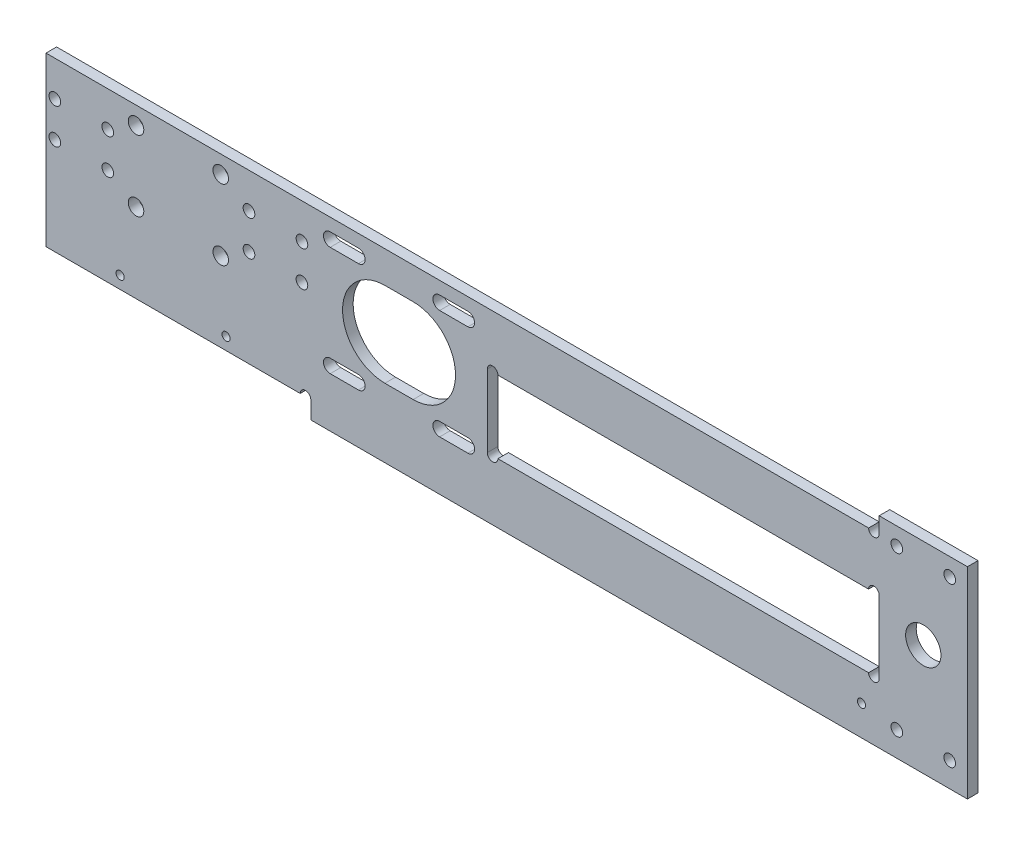
SolidWorks part; units mm, degrees
material "Thornel Mat VMA"
ref_plane "前视基准面" through (0, 0, 0) normal (0, 0, 1) x (1, 0, 0)
ref_plane "上视基准面" through (0, 0, 0) normal (0, 1, 0) x (1, 0, 0)
ref_plane "右视基准面" through (0, 0, 0) normal (1, 0, 0) x (0, 0, -1)
sketch "草图1" plane through (0, 0, 0) normal (0, 0, 1) x (1, 0, 0)
  line L1 (0, 0) -> (75, 0)
  line L2 (0, 0) -> (0, 30)
  line L3 (0, 30) -> (75, 30)
  line L4 (75, 0) -> (75, 30)
  dimension "D1" = 75
  dimension "D2" = 30
extrude "凸台-拉伸1" add sketch "草图1" along normal blind 3
sketch "草图2" plane through (0, 0, 3) normal (0, 0, 1) x (1, 0, 0)
  line L0 (0, 30) -> (75, 0)
  line L2 (25.5, 25) -> (49.5, 25)
  line L3 (25.5, 25) -> (25.5, 5)
  line L4 (25.5, 5) -> (49.5, 5)
  line L5 (49.5, 25) -> (49.5, 5)
  line L6 (25.5, 25) -> (49.5, 5) construction
  line L7 (25.5, 5) -> (49.5, 25) construction
  point P4 (37.5, 15)
  dimension "D1" = 24
  dimension "D2" = 20
sketch "草图3" plane through (0, 0, 3) normal (0, 0, 1) x (1, 0, 0)
  point P0 (25.5, 25)
  point P3 (49.5, 25)
  point P6 (49.5, 5)
  point P9 (25.5, 5)
hole_wizard "孔1" positions "草图3" profile "草图4" legacy end condition up to next
sketch "草图4" plane through (25.5, 25, 3) normal (1, 0, 0) x (0, -1, 0)
  line L0 (0, 0) -> (0, 3)
  line L1 (0, 3) -> (2.2, 3)
  line L2 (2.2, 3) -> (2.2, 0)
  line L3 (2.2, 0) -> (0, 0)
  line L4 (0, 110) -> (0, -10) construction
  dimension "直径" = 4.4
  dimension "深度" = 3
sketch "草图5" plane through (0, 0, 3) normal (0, 0, 1) x (1, 0, 0)
  line L0 (75, 30) -> (0, 30) construction
  line L1 (20, 0) -> (55, 0)
  line L2 (20, 0) -> (20, 30)
  line L3 (20, 30) -> (55, 30)
  line L4 (55, 0) -> (55, 30)
  line L5 (20, 0) -> (55, 30) construction
  line L6 (20, 30) -> (55, 0) construction
  line L7 (0, 15) -> (20, 15)
  line L8 (0, 30) -> (0, 0) construction
  line L9 (55, 15) -> (75, 15)
  line L10 (75, 0) -> (75, 30) construction
  line L12 (2.5, 10) -> (17.5, 10)
  line L13 (2.5, 10) -> (2.5, 20)
  line L14 (2.5, 20) -> (17.5, 20)
  line L15 (17.5, 10) -> (17.5, 20)
  line L16 (2.5, 10) -> (17.5, 20) construction
  line L17 (2.5, 20) -> (17.5, 10) construction
  line L18 (57.5, 10) -> (72.5, 10)
  line L19 (57.5, 10) -> (57.5, 20)
  line L20 (57.5, 20) -> (72.5, 20)
  line L21 (72.5, 10) -> (72.5, 20)
  line L22 (57.5, 10) -> (72.5, 20) construction
  line L23 (57.5, 20) -> (72.5, 10) construction
  point P0 (37.5, 15)
  point P16 (10, 15)
  point P21 (65, 15)
  dimension "D1" = 35
  dimension "D2" = 15
  dimension "D3" = 10
  dimension "D4" = 15
  dimension "D5" = 10
sketch "草图6" plane through (0, 0, 3) normal (0, 0, 1) x (1, 0, 0)
  point P0 (2.5, 20)
  point P3 (17.5, 20)
  point P6 (17.5, 10)
  point P9 (2.5, 10)
  point P12 (57.5, 10)
  point P15 (57.5, 20)
  point P18 (72.5, 20)
  point P21 (72.5, 10)
hole_wizard "孔2" positions "草图6" profile "草图7" legacy end condition up to next
sketch "草图7" plane through (2.5, 20, 3) normal (1, 0, 0) x (0, -1, 0)
  line L0 (0, 0) -> (0, 3)
  line L1 (0, 3) -> (1.65, 3)
  line L2 (1.65, 3) -> (1.65, 0)
  line L3 (1.65, 0) -> (0, 0)
  line L4 (0, 110) -> (0, -10) construction
  dimension "直径" = 3.3
  dimension "深度" = 3
sketch "草图8" plane through (0, 0, 0) normal (0, 0, -1) x (-1, 0, 0)
  line L1 (0, 30) -> (45, 30)
  line L2 (0, 30) -> (0, -12)
  line L3 (0, -12) -> (45, -12)
  line L4 (45, 30) -> (45, -12)
  dimension "D1" = 45
  dimension "D2" = 42
extrude "凸台-拉伸2" add sketch "草图8" against normal blind 3
sketch "草图9" plane through (0, 0, 3) normal (0, 0, 1) x (1, 0, 0)
  line L0 (0, -12) -> (-45, -12) construction
  line L1 (-45, 30) -> (-3, 30)
  line L2 (-45, 30) -> (-45, -12)
  line L3 (-45, -12) -> (-3, -12)
  line L4 (-3, 30) -> (-3, -12)
  line L5 (-45, 30) -> (-3, -12)
  line L7 (-39.5, 24.5) -> (-8.5, 24.5)
  line L8 (-39.5, 24.5) -> (-39.5, -6.5)
  line L9 (-39.5, -6.5) -> (-8.5, -6.5)
  line L10 (-8.5, 24.5) -> (-8.5, -6.5)
  line L11 (-39.5, 24.5) -> (-8.5, -6.5) construction
  line L12 (-39.5, -6.5) -> (-8.5, 24.5) construction
  point P7 (-24, 9)
  dimension "D1" = 42
  dimension "D2" = 31
sketch "草图10" plane through (0, 0, 3) normal (0, 0, 1) x (1, 0, 0)
  point P0 (-39.5, 24.5)
  point P3 (-8.5, 24.5)
  point P6 (-8.5, -6.5)
  point P9 (-39.5, -6.5)
hole_wizard "孔3" positions "草图10" profile "草图11" legacy end condition up to next
sketch "草图11" plane through (-39.5, 24.5, 3) normal (1, 0, 0) x (0, -1, 0)
  line L0 (0, 0) -> (0, 3)
  line L1 (0, 3) -> (1.9, 3)
  line L2 (1.9, 3) -> (1.9, 0)
  line L3 (1.9, 0) -> (0, 0)
  line L4 (0, 110) -> (0, -10) construction
  dimension "直径" = 3.8
  dimension "深度" = 3
sketch "草图12" plane through (0, 0, 0) normal (0, 0, -1) x (-1, 0, 0)
  circle A0 centre (24, 9) radius 11.5
  dimension "D1" = 23
sketch "草图13" plane through (0, 0, 0) normal (0, 0, -1) x (-1, 0, 0)
  line L0 (45, -12) -> (3, -12) construction
  line L1 (45, 30) -> (60, 30)
  line L2 (45, 30) -> (45, -12)
  line L3 (45, -12) -> (60, -12)
  line L4 (60, 30) -> (60, -12)
  dimension "D1" = 15
extrude "凸台-拉伸3" add sketch "草图13" against normal blind 3
sketch "草图14" plane through (0, 0, 0) normal (0, 0, -1) x (-1, 0, 0)
  line L0 (39.5, -6.5) -> (8.5, -6.5) construction
  line L1 (39.5, 24.5) -> (54.5, 24.5)
  line L2 (39.5, 24.5) -> (39.5, -6.5)
  line L3 (39.5, -6.5) -> (54.5, -6.5)
  line L4 (54.5, 24.5) -> (54.5, -6.5)
  line L5 (39.5, 24.5) -> (8.5, 24.5) construction
  line L7 (8.5, 26.4) -> (23.5, 26.4)
  line L8 (8.5, 26.4) -> (8.5, 22.6)
  line L9 (8.5, 22.6) -> (23.5, 22.6)
  line L10 (23.5, 26.4) -> (23.5, 22.6)
  line L11 (8.5, -4.6) -> (23.5, -4.6)
  line L12 (8.5, -4.6) -> (8.5, -8.4)
  line L13 (8.5, -8.4) -> (23.5, -8.4)
  line L14 (23.5, -4.6) -> (23.5, -8.4)
  line L15 (39.5, 26.4) -> (54.5, 26.4)
  line L16 (39.5, 26.4) -> (39.5, 22.6)
  line L17 (39.5, 22.6) -> (54.5, 22.6)
  line L18 (54.5, 26.4) -> (54.5, 22.6)
  line L19 (39.5, -4.6) -> (54.5, -4.6)
  line L20 (39.5, -4.6) -> (39.5, -8.4)
  line L21 (39.5, -8.4) -> (54.5, -8.4)
  line L22 (54.5, -4.6) -> (54.5, -8.4)
  circle A0 centre (23.5, 24.5) radius 1.9
  circle A1 centre (54.5, 24.5) radius 1.9
  circle A2 centre (54.5, -6.5) radius 1.9
  circle A3 centre (23.5, -6.5) radius 1.9
  circle A4 centre (8.5, 24.5) radius 1.9
  circle A5 centre (8.5, -6.5) radius 1.9
  circle A6 centre (39.5, 24.5) radius 1.9
  circle A7 centre (39.5, -6.5) radius 1.9
  circle M6 centre (39.5, 24.5) radius 1.9
  circle M7 centre (8.5, 24.5) radius 1.9
  circle M8 centre (8.5, -6.5) radius 1.9
  circle M9 centre (39.5, -6.5) radius 1.9
  dimension "D2" = 3.8
  dimension "D3" = 3.8
  dimension "D4" = 3.8
  dimension "D5" = 3.8
  dimension "D8" = 3.8
  dimension "D9" = 3.8
  dimension "D10" = 3.8
  dimension "D11" = 3.8
  dimension "D1" = 15
  dimension "D6" = 15
  dimension "D7" = 15
extrude "切除-拉伸3" cut sketch "草图14" against normal blind 3 contours A0 L7 L9 M7 | L10 A0 | L8 M7 | A3 L11 L13 M8 | L12 M8 | L14 A3 | L14 A3 | L12 M8 | L8 M7 | L10 A0 | A1 L15 L1 M6 | A1 L1 L17 M6 | L1 L2 M6 | L16 L1 M6 | L16 L2 M6 | L4 A1 L18 | L1 A1 L4 | L18 A1 L1 | A2 L19 L3 M9 | A2 L3 L21 M9 | L3 A2 L22 | L4 A2 L3 | L22 A2 L4 | L3 L20 M9 | L2 L3 M9 | L20 L2 M9
sketch "草图16" plane through (0, 0, 0) normal (0, 0, -1) x (-1, 0, 0)
  line L0 (24, 9) -> (39, 9)
  line L1 (39.5, 24.5) -> (39.5, -6.5) construction
  line L2 (24, 20.5041) -> (39.5, 20.5041)
  line L3 (24, 20.5041) -> (24, -2.4891)
  line L4 (24, -2.4891) -> (39.5, -2.4891)
  line L5 (39.5, 20.5041) -> (39.5, -2.4891)
  circle A0 centre (39, 9) radius 11.5
  circle A1 centre (24, 9) radius 11.5041
  dimension "D2" = 23
  dimension "D3" = 23.0082
  dimension "D1" = 15
extrude "切除-拉伸5" cut sketch "草图16" against normal blind 3
sketch "草图17" plane through (0, 0, 0) normal (0, 0, -1) x (-1, 0, 0)
  line L0 (24, 20.5041) -> (24, -2.5041)
  circle A0 centre (24, 9) radius 11.5041
  line M1 (24, -2.4891) -> (24, 20.5041)
extrude "切除-拉伸6" cut sketch "草图17" against normal blind 3 contours A0 L0 M1
sketch "草图18" plane through (0, 0, 0) normal (0, 0, -1) x (-1, 0, 0)
  line L0 (24, -2.5041) -> (-75, -2.5041)
  line L1 (-75, 0) -> (0, 0)
  line L2 (-75, 0) -> (-75, -2.5041)
  line L3 (0, 0) -> (0, -2.5041)
  line L4 (24, -2.5041) -> (-236, -2.5041)
  line L5 (24, -2.5041) -> (24, -22.5041)
  line L6 (24, -22.5041) -> (-236, -22.5041)
  line L7 (-236, -2.5041) -> (-236, -22.5041)
  line L8 (0, 0) -> (0, -12) construction
  line L9 (0, -2.5041) -> (0, -22.5041)
  line L10 (-75, -2.5041) -> (-75, -22.5041)
  line L11 (-236, -5.5041) -> (24, -5.5041)
  line L12 (-236, -5.5041) -> (-236, -22.5041)
  line L13 (-236, -22.5041) -> (24, -22.5041)
  line L14 (24, -5.5041) -> (24, -22.5041)
  circle A0 centre (24, 9) radius 11.5
  line M37 (-75, 0) -> (0, 0)
  line M38 (0, 0) -> (0, -12)
  dimension "D1" = 23
  dimension "D2" = 99
  dimension "D3" = 260
  dimension "D4" = 20
  dimension "D5" = 17
extrude "凸台-拉伸4" add sketch "草图18" against normal blind 3 contours L2 L0 M37 M38 | L10 L11 L0 M38 | L11 L10 L6 L9 | L11 L7 L6 L10
sketch "草图19" plane through (0, 0, 3) normal (0, 0, 1) x (1, 0, 0)
  line L0 (0, -22.5041) -> (236, -22.5041) construction
  line L1 (236, -5.5041) -> (46, -5.5041)
  line L2 (236, -5.5041) -> (236, -22.5041)
  line L3 (236, -22.5041) -> (46, -22.5041)
  line L4 (46, -5.5041) -> (46, -22.5041)
  line L5 (236, -14.0041) -> (46, -14.0041)
  point P9 (231, -14.0041)
  point P10 (51, -14.0041)
  dimension "D1" = 190
  dimension "D2" = 5
  dimension "D3" = 5
sketch "草图20" plane through (0, 0, 3) normal (0, 0, 1) x (1, 0, 0)
  point P0 (80, -14.0041)
  point P2 (260, -14.0041)
  point P4 (231, -14.0041)
  point P7 (51, -14.0041)
hole_wizard "孔4" positions "草图20" profile "草图21" legacy
sketch "草图21" plane through (51, -14.0041, 3) normal (1, 0, 0) x (0, -1, 0)
  line L0 (0, 0) -> (0, 3)
  line L1 (0, 3) -> (1.15, 3)
  line L2 (1.15, 3) -> (1.15, 0)
  line L3 (1.15, 0) -> (0, 0)
  line L4 (0, 110) -> (0, -10) construction
  dimension "直径" = 2.3
  dimension "深度" = 3
sketch "草图22" plane through (0, 0, 0) normal (0, 0, -1) x (-1, 0, 0)
  line L1 (-236, 19.4959) -> (-261, 19.4959)
  line L2 (-236, 19.4959) -> (-236, -22.5041)
  line L3 (-236, -22.5041) -> (-261, -22.5041)
  line L4 (-261, 19.4959) -> (-261, -22.5041)
  line L5 (-236, -5.5041) -> (-236, -22.5041) construction
  line L6 (-236, -22.5041) -> (-46, -22.5041) construction
  dimension "D1" = 42
  dimension "D2" = 25
extrude "凸台-拉伸5" add sketch "草图22" against normal up to vertex (3 mm away) up to point (236, -22.5041, 3)
sketch "草图23" plane through (0, 0, 0) normal (0, 0, -1) x (-1, 0, 0)
  line L0 (-261, 19.4959) -> (-261, -22.5041) construction
  line L1 (-261, 19.4959) -> (-236, 19.4959)
  line L2 (-261, 19.4959) -> (-261, -5.5041)
  line L3 (-261, -5.5041) -> (-236, -5.5041)
  line L4 (-236, 19.4959) -> (-236, -5.5041)
  line L5 (-236, -5.5041) -> (-236, 19.4959) construction
  line L6 (-236, 19.4959) -> (-261, 19.4959) construction
  line L7 (-236, 19.4959) -> (-261, -5.5041)
  line L8 (-248.5, 6.9959) -> (-248.5, 8.9959)
  dimension "D1" = 2
sketch "草图24" plane through (0, 0, 0) normal (0, 0, -1) x (-1, 0, 0)
  point P0 (-277.5, 6.9959)
  point P2 (-248.5, 8.9959)
hole_wizard "孔5" positions "草图24" profile "草图25" legacy end condition up to next
sketch "草图25" plane through (248.5, 8.9959, 0) normal (1, 0, 0) x (0, 1, 0)
  line L0 (0, 0) -> (0, 3)
  line L1 (0, 3) -> (5, 3)
  line L2 (5, 3) -> (5, 0)
  line L3 (5, 0) -> (0, 0)
  line L4 (0, 110) -> (0, -10) construction
  dimension "直径" = 10
  dimension "深度" = 3
sketch "草图26" plane through (0, 0, 0) normal (0, 0, -1) x (-1, 0, 0)
  line L1 (-261, -10.5041) -> (-251, -10.5041)
  line L2 (-261, -10.5041) -> (-261, -20.5041)
  line L3 (-261, -20.5041) -> (-251, -20.5041)
  line L4 (-251, -10.5041) -> (-251, -20.5041)
  line L5 (-261, -10.5041) -> (-251, -20.5041)
  line L6 (-236, -10.5041) -> (-246, -10.5041)
  line L7 (-236, -10.5041) -> (-236, -20.5041)
  line L8 (-236, -20.5041) -> (-246, -20.5041)
  line L9 (-246, -10.5041) -> (-246, -20.5041)
  line L10 (-236, -10.5041) -> (-246, -20.5041)
  line L11 (-261, -5.5041) -> (-236, -5.5041) construction
  line L12 (-261, 19.4959) -> (-261, -22.5041) construction
  line L13 (-236, -5.5041) -> (-236, -22.5041) construction
  dimension "D1" = 10
  dimension "D2" = 10
  dimension "D3" = 10
  dimension "D4" = 10
  dimension "D5" = 5
  dimension "D6" = 5
sketch "草图29" plane through (0, 0, 0) normal (0, 0, -1) x (-1, 0, 0)
  line L0 (-261, -10.5041) -> (-251, -20.5041) construction
  line L1 (-236, -10.5041) -> (-246, -20.5041) construction
  point P0 (-285, -15.5041)
  point P2 (-270, -15.5041)
  point P3 (-285, -15.5041)
  point P6 (-285, -15.5041)
  point P9 (-256, -15.5041)
  point P13 (-241, -15.5041)
hole_wizard "孔7" positions "草图29" profile "草图30" legacy end condition up to next
sketch "草图30" plane through (241, -15.5041, 0) normal (1, 0, 0) x (0, 1, 0)
  line L0 (0, 0) -> (0, 3.001)
  line L1 (0, 3.001) -> (1.65, 3.001)
  line L2 (1.65, 3.001) -> (1.65, 0)
  line L3 (1.65, 0) -> (0, 0)
  line L4 (0, 110) -> (0, -10) construction
  dimension "直径" = 3.3
  dimension "深度" = 3.001
sketch "草图31" plane through (0, 0, 0) normal (0, 0, -1) x (-1, 0, 0)
  line L0 (-236, 19.4959) -> (-236, -5.5041) construction
  line L1 (-261, 19.4959) -> (-236, 19.4959)
  line L2 (-261, 19.4959) -> (-261, 34.4959)
  line L3 (-261, 34.4959) -> (-236, 34.4959)
  line L4 (-236, 19.4959) -> (-236, 34.4959)
  line L5 (-261, 19.4959) -> (-261, -5.5041) construction
  line L6 (-261, 19.4959) -> (-236, 19.4959) construction
  dimension "D1" = 15
extrude "凸台-拉伸6" add sketch "草图31" against normal blind 3
sketch "草图32" plane through (0, 0, 0) normal (0, 0, -1) x (-1, 0, 0)
  line L0 (-261, 34.4959) -> (-261, -22.5041) construction
  line L1 (-261, 34.4959) -> (-251, 34.4959)
  line L2 (-261, 34.4959) -> (-261, 24.4959)
  line L3 (-261, 24.4959) -> (-251, 24.4959)
  line L4 (-251, 34.4959) -> (-251, 24.4959)
  line L5 (-236, 34.4959) -> (-261, 34.4959) construction
  line L6 (-236, -5.5041) -> (-236, 34.4959) construction
  line L7 (-236, 34.4959) -> (-246, 34.4959)
  line L8 (-236, 34.4959) -> (-236, 24.4959)
  line L9 (-236, 24.4959) -> (-246, 24.4959)
  line L10 (-246, 34.4959) -> (-246, 24.4959)
  line L11 (-261, 34.4959) -> (-251, 24.4959)
  line L12 (-236, 34.4959) -> (-246, 24.4959)
  dimension "D1" = 10
  dimension "D2" = 10
  dimension "D3" = 10
  dimension "D4" = 10
sketch "草图33" plane through (0, 0, 0) normal (0, 0, -1) x (-1, 0, 0)
  line L0 (-261, 34.4959) -> (-251, 24.4959) construction
  line L1 (-236, 34.4959) -> (-246, 24.4959) construction
  point P0 (-285, 29.4959)
  point P2 (-270, 29.4959)
  point P3 (-256, 29.4959)
  point P7 (-241, 29.4959)
hole_wizard "孔8" positions "草图33" profile "草图34" legacy end condition up to next
sketch "草图34" plane through (241, 29.4959, 0) normal (1, 0, 0) x (0, 1, 0)
  line L0 (0, 0) -> (0, 3)
  line L1 (0, 3) -> (1.65, 3)
  line L2 (1.65, 3) -> (1.65, 0)
  line L3 (1.65, 0) -> (0, 0)
  line L4 (0, 110) -> (0, -10) construction
  dimension "直径" = 3.3
  dimension "深度" = 3
sketch "草图35" plane through (0, 0, 0) normal (0, 0, -1) x (-1, 0, 0)
  line L0 (24, 9) -> (-261, 9)
  line L1 (-236, -22.5041) -> (-46, -22.5041) construction
  line L2 (-261, 19.4959) -> (-261, -5.5041) construction
sketch "草图36" plane through (0, 0, 0) normal (0, 0, -1) x (-1, 0, 0)
  line L0 (-236, 19.4959) -> (-236, -5.5041) construction
  line L1 (-75, 30) -> (-236, 30)
  line L2 (-75, 30) -> (-75, 15)
  line L3 (-75, 15) -> (-236, 15)
  line L4 (-236, 30) -> (-236, 15)
  dimension "D1" = 15
extrude "凸台-拉伸7" add sketch "草图36" against normal blind 3
sketch "草图37" plane through (0, 0, 0) normal (0, 0, -1) x (-1, 0, 0)
  line L0 (-51, -14.0041) -> (-21, -14.0041)
  dimension "D1" = 30
sketch "草图38" plane through (0, 0, 0) normal (0, 0, -1) x (-1, 0, 0)
  point P0 (-21, -14.0041)
hole_wizard "孔9" positions "草图38" profile "草图39" legacy end condition up to next
sketch "草图39" plane through (21, -14.0041, 0) normal (1, 0, 0) x (0, 1, 0)
  line L0 (0, 0) -> (0, 3)
  line L1 (0, 3) -> (1.15, 3)
  line L2 (1.15, 3) -> (1.15, 0)
  line L3 (1.15, 0) -> (0, 0)
  line L4 (0, 110) -> (0, -10) construction
  dimension "直径" = 2.3
  dimension "深度" = 3
sketch "草图40" plane through (0, 0, 0) normal (0, 0, -1) x (-1, 0, 0)
  line L0 (39.5, -6.5) -> (8.5, 24.5) construction
  line L1 (24, 21) -> (39, 21)
  line L2 (24, -3) -> (39, -3)
  circle A0 centre (24, 9) radius 12
  circle A1 centre (39, 9) radius 12
  dimension "D1" = 24
  dimension "D2" = 24
extrude "切除-拉伸7" cut sketch "草图40" against normal blind 10 contours A1 A0 | A0 A1 | A1 L1 A0 | A1 A0 | A1 A0 L2
sketch "草图41" plane through (0, 0, 0) normal (0, 0, -1) x (-1, 0, 0)
  line L0 (24, 9) -> (-261, 9) construction
  line L1 (-125, -12) -> (-75, -12)
  line L2 (-125, -12) -> (-125, 30)
  line L3 (-125, 30) -> (-75, 30)
  line L4 (-75, -12) -> (-75, 30)
  line L5 (-125, -12) -> (-75, 30) construction
  line L6 (-125, 30) -> (-75, -12) construction
  line L7 (-75, -5.5041) -> (-75, 15) construction
  line L8 (-236, 15) -> (-75, 15) construction
  line L9 (-125, 15) -> (-75, 15)
  line L10 (-125, 15) -> (-125, -5.5041)
  line L11 (-125, -5.5041) -> (-75, -5.5041)
  line L12 (-75, 15) -> (-75, -5.5041)
  point P0 (-100, 9)
  dimension "D1" = 50
  dimension "D2" = 42
extrude "凸台-拉伸8" add sketch "草图41" against normal blind 3 contours L2 L11 L4 L9
sketch "草图42" plane through (0, 0, 0) normal (0, 0, -1) x (-1, 0, 0)
  line L0 (-125, -5.5041) -> (-125, 30)
  line L1 (-236, 30) -> (60, 30) construction
  line L2 (-125, 30) -> (-83, -12)
  line L3 (-125, 30) -> (-75, 30)
  line L4 (-125, 30) -> (-125, -12)
  line L5 (-125, -12) -> (-75, -12)
  line L6 (-75, 30) -> (-75, -12)
  line L7 (-125, 30) -> (-83, 30)
  line L8 (-125, 30) -> (-125, -12)
  line L9 (-125, -12) -> (-83, -12)
  line L10 (-83, 30) -> (-83, -12)
  line L11 (-88.5, 24.5) -> (-80.5, 24.5)
  line L12 (-119.5, -6.5) -> (-88.5, -6.5)
  line L13 (-119.5, -6.5) -> (-119.5, 24.5)
  line L14 (-119.5, 24.5) -> (-88.5, 24.5)
  line L15 (-88.5, -6.5) -> (-88.5, 24.5)
  line L16 (-119.5, -6.5) -> (-88.5, 24.5) construction
  line L17 (-119.5, 24.5) -> (-88.5, -6.5) construction
  line L18 (-88.5, -6.5) -> (-80.5, -6.5)
  line L19 (-104, 9) -> (-96, 9)
  line L20 (24, 9) -> (-261, 9) construction
  point P10 (-104, 9)
  point P15 (-111.5, 24.5)
  point P18 (-111.5, -6.5)
  dimension "D1" = 50
  dimension "D2" = 42
  dimension "D3" = 42
  dimension "D4" = 31
  dimension "D5" = 8
  dimension "D6" = 8
  dimension "D7" = 8
  dimension "D8" = 8
  dimension "D9" = 8
sketch "草图44" plane through (0, 0, 0) normal (0, 0, -1) x (-1, 0, 0)
  point P0 (-119.5, 24.5)
  point P3 (-111.5, 24.5)
  point P6 (-88.5, 24.5)
  point P9 (-80.5, 24.5)
  point P12 (-88.5, -6.5)
  point P15 (-80.5, -6.5)
  point P18 (-119.5, -6.5)
  point P21 (-111.5, -6.5)
hole_wizard "孔10" positions "草图44" profile "草图45" legacy end condition through all
sketch "草图45" plane through (119.5, 24.5, 0) normal (1, 0, 0) x (0, 1, 0)
  line L0 (0, 0) -> (0, 3)
  line L1 (0, 3) -> (1.9, 3)
  line L2 (1.9, 3) -> (1.9, 0)
  line L3 (1.9, 0) -> (0, 0)
  line L4 (0, 110) -> (0, -10) construction
  dimension "直径" = 3.8
  dimension "深度" = 3
sketch "草图46" plane through (0, 0, 0) normal (0, 0, -1) x (-1, 0, 0)
  point P0 (-104, 9)
  point P3 (-96, 9)
hole_wizard "孔11" positions "草图46" profile "草图47" legacy end condition through all
sketch "草图47" plane through (104, 9, 0) normal (1, 0, 0) x (0, 1, 0)
  line L0 (0, 0) -> (0, 3)
  line L1 (0, 3) -> (12, 3)
  line L2 (12, 3) -> (12, 0)
  line L3 (12, 0) -> (0, 0)
  line L4 (0, 110) -> (0, -10) construction
  dimension "直径" = 24
  dimension "深度" = 3
sketch "草图48" plane through (0, 0, 0) normal (0, 0, -1) x (-1, 0, 0)
  line L0 (-119.5, 26.4) -> (-111.5, 26.4)
  line L1 (-111.5, 26.4) -> (-111.5, 22.6)
  line L2 (-111.5, 22.6) -> (-119.5, 22.6)
  line L3 (-119.5, -6.5) -> (-119.5, 24.5) construction
  line L4 (-119.5, 22.6) -> (-119.5, 26.4)
  line L5 (-88.5, 26.4) -> (-80.5, 26.4)
  line L6 (-80.5, 26.4) -> (-80.5, 22.6)
  line L7 (-80.5, 22.6) -> (-88.5, 22.6)
  line L8 (-88.5, -6.5) -> (-88.5, 24.5) construction
  line L9 (-88.5, 22.6) -> (-88.5, 26.4)
  line L10 (-119.5, -4.6) -> (-111.5, -4.6)
  line L11 (-111.5, -4.6) -> (-111.5, -8.4)
  line L12 (-111.5, -8.4) -> (-119.5, -8.4)
  line L13 (-119.5, -8.4) -> (-119.5, -4.6)
  line L14 (-88.5, -4.6) -> (-80.5, -4.6)
  line L15 (-80.5, -4.6) -> (-80.5, -8.4)
  line L16 (-80.5, -8.4) -> (-88.5, -8.4)
  line L17 (-88.5, -8.4) -> (-88.5, -4.6)
  line L18 (-104, 21) -> (-96, 21)
  line L19 (-96, 21) -> (-96, -3)
  line L20 (-96, -3) -> (-104, -3)
  line L21 (-104, -3) -> (-104, 21)
  circle A0 centre (-119.5, 24.5) radius 1.9 construction
  circle A1 centre (-111.5, 24.5) radius 1.9 construction
  circle A2 centre (-88.5, 24.5) radius 1.9 construction
  circle A3 centre (-80.5, 24.5) radius 1.9 construction
  circle A4 centre (-119.5, -6.5) radius 1.9 construction
  circle A5 centre (-111.5, -6.5) radius 1.9 construction
  circle A6 centre (-88.5, -6.5) radius 1.9 construction
  circle A7 centre (-80.5, -6.5) radius 1.9 construction
  arc A8 (-100, 20.3137) -> (-100, -2.3137) centre (-104, 9) ccw construction
  arc A9 (-100, -2.3137) -> (-100, 20.3137) centre (-96, 9) ccw construction
extrude "切除-拉伸8" cut sketch "草图48" against normal blind 3
sketch "草图49" plane through (0, 0, 0) normal (0, 0, -1) x (-1, 0, 0)
  line L1 (3, 30) -> (60, 30)
  line L2 (3, 30) -> (3, -12)
  line L3 (3, -12) -> (60, -12)
  line L4 (60, 30) -> (60, -12)
extrude "切除-拉伸9" cut sketch "草图49" against normal blind 3
sketch "草图50" plane through (0, 0, 0) normal (0, 0, -1) x (-1, 0, 0)
  line L1 (3, -12) -> (0, -12)
  line L2 (3, -12) -> (3, 30)
  line L3 (3, 30) -> (0, 30)
  line L4 (0, -12) -> (0, 30)
extrude "切除-拉伸10" cut sketch "草图50" against normal blind 3
sketch "草图51" plane through (0, 0, 0) normal (0, 0, -1) x (-1, 0, 0)
  line L1 (0, -22.5041) -> (-75, -22.5041)
  line L2 (0, -22.5041) -> (0, -17.5041)
  line L3 (0, -17.5041) -> (-75, -17.5041)
  line L4 (-75, -22.5041) -> (-75, -17.5041)
  dimension "D1" = 5
  dimension "D2" = 75
extrude "切除-拉伸11" cut sketch "草图51" against normal blind 10
sketch "草图52" plane through (0, 0, 0) normal (0, 0, -1) x (-1, 0, 0)
  line L0 (-236, 15) -> (-234.5, 15)
  line L1 (-236, 15) -> (-125, 15) construction
  line L2 (-236, -5.5041) -> (-234.5, -5.5041)
  line L3 (-236, -5.5041) -> (-46, -5.5041) construction
  line L4 (-125, 15) -> (-126.5, 15)
  line L5 (-125, -5.5041) -> (-126.5, -5.5041)
  dimension "D1" = 1.5
  dimension "D2" = 1.5
  dimension "D3" = 1.5
  dimension "D4" = 1.5
sketch "草图53" plane through (0, 0, 0) normal (0, 0, -1) x (-1, 0, 0)
  point P0 (-234.5, 15)
  point P3 (-234.5, -5.5041)
  point P6 (-126.5, -5.5041)
  point P9 (-126.5, 15)
hole_wizard "孔12" positions "草图53" profile "草图54" legacy end condition up to next
sketch "草图54" plane through (234.5, 15, 0) normal (1, 0, 0) x (0, 1, 0)
  line L0 (0, 0) -> (0, 3)
  line L1 (0, 3) -> (1.5, 3)
  line L2 (1.5, 3) -> (1.5, 0)
  line L3 (1.5, 0) -> (0, 0)
  line L4 (0, 110) -> (0, -10) construction
  dimension "直径" = 3
  dimension "深度" = 3
sketch "草图55" plane through (0, 0, 0) normal (0, 0, -1) x (-1, 0, 0)
  line L0 (-75, -17.5041) -> (-73.5, -17.5041)
  line L1 (0, -17.5041) -> (-75, -17.5041) construction
  line L2 (-236, 30) -> (-234.5, 30)
  line L3 (-236, 30) -> (0, 30) construction
  dimension "D1" = 1.5
  dimension "D2" = 1.5
sketch "草图56" plane through (0, 0, 0) normal (0, 0, -1) x (-1, 0, 0)
  point P0 (-234.5, 30)
  point P3 (-73.5, -17.5041)
hole_wizard "孔13" positions "草图56" profile "草图57" legacy end condition up to next
sketch "草图57" plane through (234.5, 30, 0) normal (1, 0, 0) x (0, 1, 0)
  line L0 (0, 0) -> (0, 3)
  line L1 (0, 3) -> (1.5, 3)
  line L2 (1.5, 3) -> (1.5, 0)
  line L3 (1.5, 0) -> (0, 0)
  line L4 (0, 110) -> (0, -10) construction
  dimension "直径" = 3
  dimension "深度" = 3
